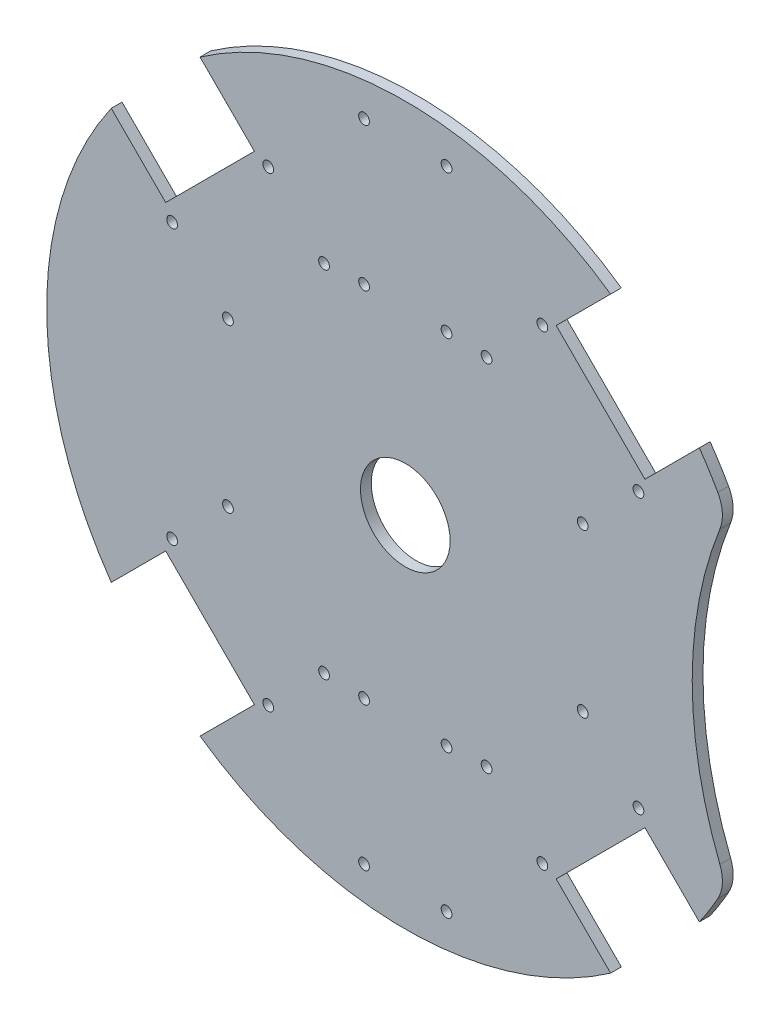
SolidWorks part; units mm, degrees
ref_plane "Alzado" through (0, 0, 0) normal (0, 0, 1) x (1, 0, 0)
ref_plane "Planta" through (0, 0, 0) normal (0, 1, 0) x (1, 0, 0)
ref_plane "Vista lateral" through (0, 0, 0) normal (1, 0, 0) x (0, 0, -1)
sketch "Croquis1" plane through (0, 0, 0) normal (0, 0, 1) x (1, 0, 0)
  circle A0 centre (0, 0) radius 100
  dimension "D1" = 200
extrude "Saliente-Extruir1" add sketch "Croquis1" along normal blind 3
sketch "Croquis3" plane through (0, 0, 3) normal (0, 0, 1) x (1, 0, 0)
  line L0 (0, 0) -> (190, 0) construction
  circle A0 centre (190, 0) radius 110
  dimension "D1" = 220
  dimension "D2" = 190
extrude "Cortar-Extruir1" cut sketch "Croquis3" against normal blind 3
fillet "Redondeo1" radius 10 2 edges at (89.4737, -44.6594, 1.5) (89.4737, 44.6594, 1.5)
sketch "Croquis4" plane through (0, 0, 3) normal (0, 0, 1) x (1, 0, 0)
  line L0 (-100, 0) -> (80, 0) construction
  line L1 (0, 0) -> (0, -100) construction
  line L2 (-54.4472, -54.4472) -> (-51.6188, -51.6188) construction
  line L3 (-58.3363, -83.085) -> (-83.085, -58.3363)
  line L4 (-66.8216, 42.0729) -> (-42.0729, 66.8216)
  line L5 (-83.085, -58.3363) -> (-66.8216, -42.0729)
  line L6 (-58.3363, -83.085) -> (-42.0729, -66.8216)
  line L7 (-42.0729, -66.8216) -> (-66.8216, -42.0729)
  line L8 (-58.3363, 83.085) -> (-42.0729, 66.8216)
  line L9 (-83.085, 58.3363) -> (-58.3363, 83.085)
  line L10 (-83.085, 58.3363) -> (-66.8216, 42.0729)
  line L11 (42.0729, 66.8216) -> (66.8216, 42.0729)
  line L12 (83.085, 58.3363) -> (66.8216, 42.0729)
  line L13 (58.3363, 83.085) -> (83.085, 58.3363)
  line L14 (58.3363, 83.085) -> (42.0729, 66.8216)
  line L15 (66.8216, -42.0729) -> (42.0729, -66.8216)
  line L16 (58.3363, -83.085) -> (42.0729, -66.8216)
  line L17 (83.085, -58.3363) -> (58.3363, -83.085)
  line L18 (83.085, -58.3363) -> (66.8216, -42.0729)
  arc A0 (87.1345, 49.0671) -> (87.1345, -49.0671) centre (0, 0) ccw construction
  arc A1 (87.7193, 40.4803) -> (87.7193, -40.4803) centre (190, 0) ccw construction
  circle A2 centre (-65.0185, -38.2191) radius 1.5
  circle A3 centre (-49.4621, -22.6628) radius 1.5
  circle A4 centre (-22.6628, -49.4621) radius 1.5
  circle A5 centre (-38.2191, -65.0185) radius 1.5
  circle A6 centre (-22.6628, 49.4621) radius 1.5
  circle A7 centre (-38.2191, 65.0185) radius 1.5
  circle A8 centre (-49.4621, 22.6628) radius 1.5
  circle A9 centre (-65.0185, 38.2191) radius 1.5
  circle A10 centre (49.4621, 22.6628) radius 1.5
  circle A11 centre (65.0185, 38.2191) radius 1.5
  circle A12 centre (22.6628, 49.4621) radius 1.5
  circle A13 centre (38.2191, 65.0185) radius 1.5
  circle A14 centre (22.6628, -49.4621) radius 1.5
  circle A15 centre (38.2191, -65.0185) radius 1.5
  circle A16 centre (49.4621, -22.6628) radius 1.5
  circle A17 centre (65.0185, -38.2191) radius 1.5
  circle A18 centre (0, 0) radius 12.5
  point P64 (0, 0)
  dimension "D5" = 3
  dimension "D6" = 3
  dimension "D7" = 3
  dimension "D8" = 22
  dimension "D9" = 3
  dimension "D10" = 37.9
  dimension "D11" = 22
  dimension "D12" = 37.9
  dimension "D14" = 54.4068
  dimension "D17" = 25
  dimension "D1" = 35
  dimension "D2" = 23
  dimension "D3" = 23
  dimension "D4" = 17.5
  dimension "D13" = 4
  dimension "D15" = 77
  dimension "D16" = 4
extrude "Cortar-Extruir2" cut sketch "Croquis4" against normal through all
sketch "Croquis5" plane through (0, 0, 0) normal (0, 0, -1) x (-1, 0, 0)
  line L0 (0, -100) -> (0, -90) construction
  line L1 (11.5, -90) -> (-11.5, -90) construction
  line L3 (-11.5, -90) -> (-11.5, -50) construction
  line L4 (0, 0) -> (0, -100) construction
  line L5 (-11.5, -50) -> (11.5, -50) construction
  line L6 (11.5, -50) -> (11.5, -90) construction
  circle A0 centre (11.5, -90) radius 1.5
  circle A1 centre (-11.5, -90) radius 1.5
  circle A2 centre (-11.5, -50) radius 1.5
  circle A3 centre (11.5, -50) radius 1.5
  arc A5 (-57.2451, -81.9939) -> (57.2451, -81.9939) centre (0, 0) ccw construction
  circle A9 centre (-11.5, 90) radius 1.5
  circle A10 centre (11.5, 90) radius 1.5
  circle A11 centre (11.5, 50) radius 1.5
  circle A12 centre (-11.5, 50) radius 1.5
  circle A25 centre (90, 11.5) radius 1.5 [skipped]
  circle A26 centre (90, -11.5) radius 1.5 [skipped]
  circle A27 centre (50, 11.5) radius 1.5 [skipped]
  circle A28 centre (50, -11.5) radius 1.5 [skipped]
  circle A29 centre (-90, -11.5) radius 1.5 [skipped]
  circle A30 centre (-90, 11.5) radius 1.5 [skipped]
  circle A31 centre (-50, 11.5) radius 1.5 [skipped]
  circle A32 centre (-50, -11.5) radius 1.5 [skipped]
  point P41 (0, 0)
  point P59 (0, 0)
  dimension "D1" = 23
  dimension "D3" = 3
  dimension "D4" = 3
  dimension "D5" = 3
  dimension "D6" = 3
  dimension "D2" = 40
  dimension "D7" = 4
extrude "Cortar-Extruir3" cut sketch "Croquis5" against normal through all
